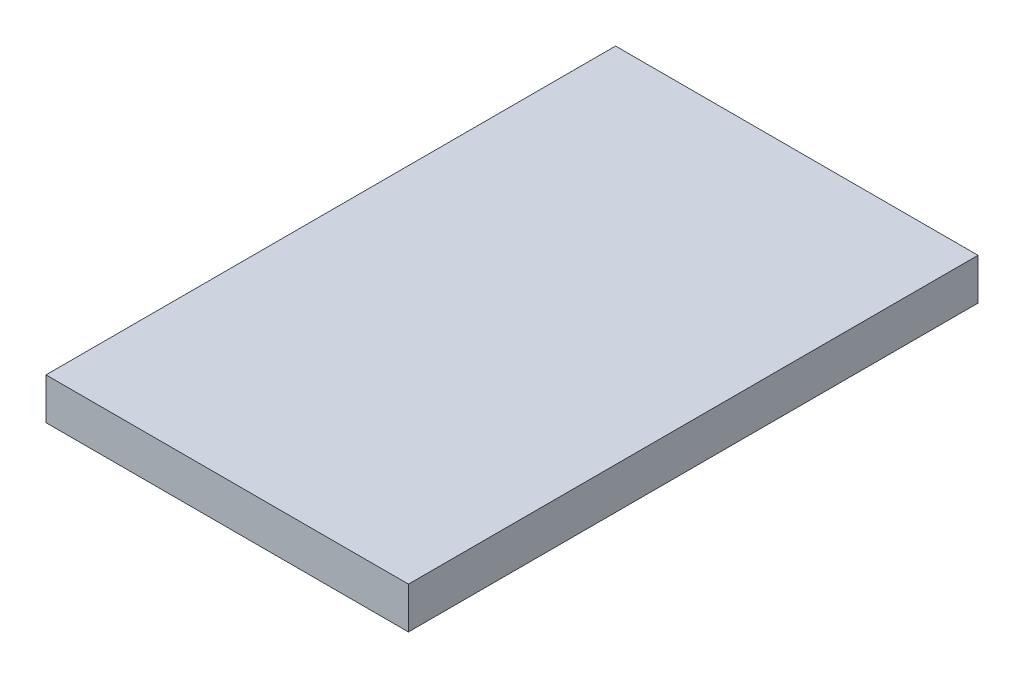
SolidWorks part; units mm, degrees
ref_plane "Front Plane" through (0, 0, 0) normal (0, 0, 1) x (1, 0, 0)
ref_plane "Top Plane" through (0, 0, 0) normal (0, 1, 0) x (1, 0, 0)
ref_plane "Right Plane" through (0, 0, 0) normal (1, 0, 0) x (0, 0, -1)
sketch "Sketch1" plane through (0, 0, 0) normal (0, 1, 0) x (1, 0, 0)
  line L1 (0, 0) -> (35, 0)
  line L2 (0, 0) -> (0, -55)
  line L3 (0, -55) -> (35, -55)
  line L4 (35, 0) -> (35, -55)
  dimension "D1" = 55
  dimension "D2" = 35
extrude "Boss-Extrude1" add sketch "Sketch1" along normal blind 4
